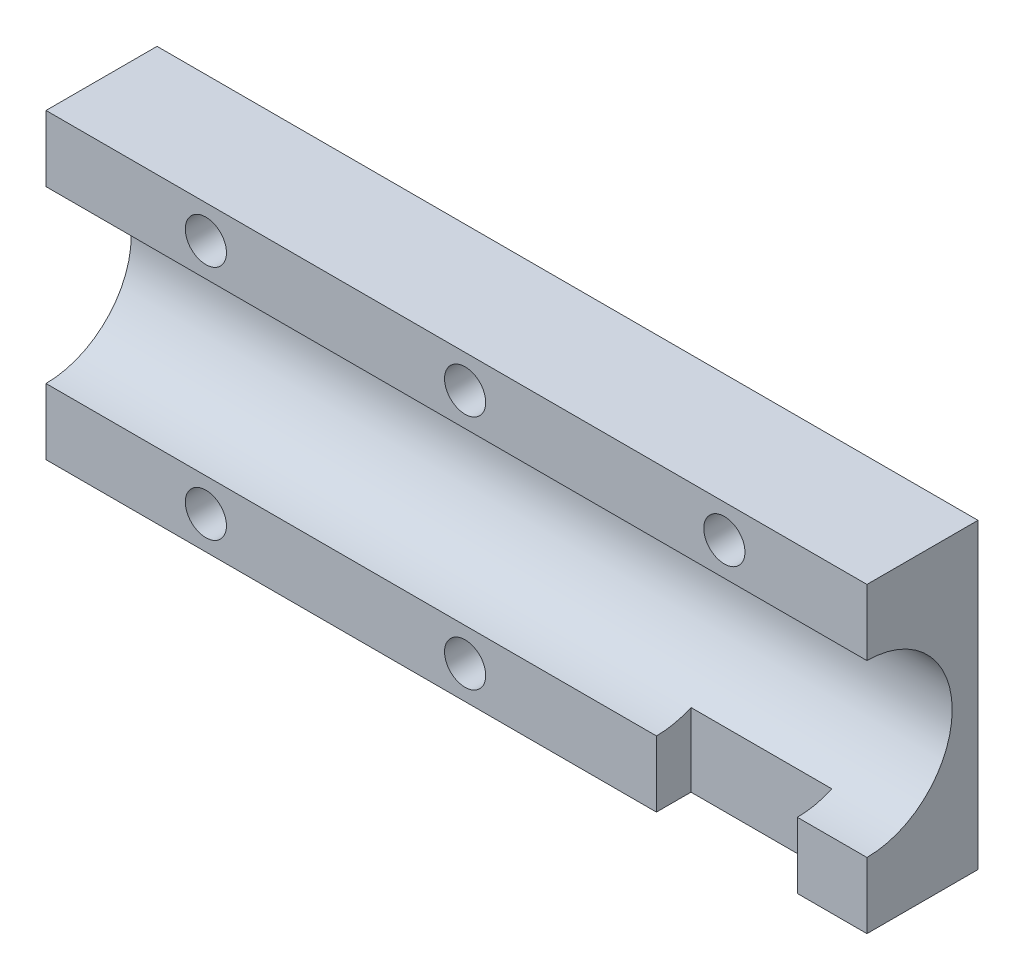
SolidWorks part; units mm, degrees
material "ABS"
ref_plane "X-Y Datum" through (0, 0, 0) normal (0, 0, 1) x (1, 0, 0)
ref_plane "X-Z Datum" through (0, 0, 0) normal (0, 1, 0) x (1, 0, 0)
ref_plane "Y-Z Datum" through (0, 0, 0) normal (1, 0, 0) x (0, 0, -1)
sketch "Sketch1" plane through (0, 0, 0) normal (0, 0, 1) x (1, 0, 0)
  line L1 (-59.055, 22.225) -> (59.055, 22.225)
  line L2 (-59.055, 22.225) -> (-59.055, -22.225)
  line L3 (-59.055, -22.225) -> (59.055, -22.225)
  line L4 (59.055, 22.225) -> (59.055, -22.225)
  line L5 (-59.055, 22.225) -> (59.055, -22.225) construction
  line L6 (-59.055, -22.225) -> (59.055, 22.225) construction
  point P0 (0, 0)
  dimension "D1" = 118.11
  dimension "D2" = 44.45
extrude "Boss-Extrude1" add sketch "Sketch1" along normal blind 2
sketch "Sketch2" plane through (-59.055, 0, 0) normal (-1, 0, 0) x (0, 0, 1)
  line L0 (2, -22.225) -> (0, -22.225) construction
  line L1 (2, 22.225) -> (16.3195, 22.225)
  line L2 (2, 22.225) -> (2, -22.225)
  line L3 (2, -22.225) -> (16.3195, -22.225)
  line L4 (16.3195, 22.225) -> (16.3195, -22.225)
  circle A0 centre (16.3195, 0) radius 12.0269 construction
  circle A1 centre (16.3195, 0) radius 12.0269 construction
  circle A2 centre (16.3195, 0) radius 12.5269
  line M9 (2, -22.225) -> (2, 22.225)
  dimension "D2" = 14.3195
  dimension "D1" = 0.5
extrude "Boss-Extrude2" add sketch "Sketch2" against normal blind 118.11 and the other way blind 2.54 contours A2 L4 L1 L3 M9
sketch "Sketch3" plane through (0, 0, 16.3195) normal (0, 0, 1) x (1, 0, 0)
  line L0 (-57.15, 17.376) -> (57.15, 17.376) construction
  circle A0 centre (0, 17.376) radius 3.025
  dimension "D1" = 6.05
extrude "Cut-Extrude1" cut sketch "Sketch3" against normal blind 8
sketch "Sketch4" [suppressed] plane through (0, 0, 0) normal (0, 0, 1) x (1, 0, 0)
  line L0 (55.5625, -20.6375) -> (65.7225, -30.7975) construction
  line L5 (-65.7225, 20.6375) -> (-55.5625, 20.6375)
  line L6 (-65.7225, 20.6375) -> (-65.7225, 30.7975)
  line L7 (-65.7225, 30.7975) -> (-55.5625, 30.7975)
  line L8 (-55.5625, 20.6375) -> (-55.5625, 30.7975)
  line L9 (55.5625, -30.7975) -> (65.7225, -30.7975)
  line L10 (55.5625, -30.7975) -> (55.5625, -20.6375)
  line L11 (55.5625, -20.6375) -> (65.7225, -20.6375)
  line L12 (65.7225, -30.7975) -> (65.7225, -20.6375)
  line L13 (-65.7225, 30.7975) -> (-55.5625, 20.6375)
  line L14 (49.022, 22.225) -> (-57.15, 22.225) construction
  line L17 (49.022, -22.225) -> (-57.15, -22.225) construction
  line L18 (-55.5625, 30.7975) -> (-46.99, 22.225)
  line L19 (-65.7225, 20.6375) -> (-55.5625, 30.7975)
  line L20 (-65.7225, 20.6375) -> (-57.15, 12.065)
  line L21 (55.5625, -30.7975) -> (46.99, -22.225)
  line L22 (65.7225, -20.6375) -> (55.5625, -30.7975) construction
  line L23 (65.7225, -20.6375) -> (57.15, -12.065)
  line L24 (57.15, -10.7701) -> (49.022, -22.225)
  line L25 (49.022, -22.225) -> (-57.15, -22.225)
  line L26 (-57.15, 22.225) -> (-57.15, 10.3851)
  line L27 (49.022, 22.225) -> (-57.15, 22.225)
  circle A0 centre (60.6425, -25.7175) radius 2 construction
  circle A1 centre (-60.6425, 25.7175) radius 2 construction
  dimension "D1" = 4
  dimension "D2" = 4
  dimension "D3" = 10.16
  dimension "D4" = 10.16
  dimension "D5" = 10.16
  dimension "D6" = 10.16
  dimension "D7" = 1.5875
  dimension "D10" = 1.5875
sketch "Sketch11" plane through (0, 0, 16.3195) normal (0, 0, 1) x (1, 0, 0)
  line L0 (59.055, -12.5269) -> (-61.595, -12.5269) construction
  line L1 (28.1163, -12.5269) -> (48.8246, -12.5269)
  line L2 (28.1163, -12.5269) -> (28.1163, -22.225)
  line L3 (28.1163, -22.225) -> (48.8246, -22.225)
  line L4 (48.8246, -12.5269) -> (48.8246, -22.225)
  line L5 (59.055, -22.225) -> (-61.595, -22.225) construction
extrude "Cut-Extrude4" cut sketch "Sketch11" against normal blind 5.08
sketch "Sketch12" plane through (0, -12.5269, 0) normal (0, -1, 0) x (1, 0, 0)
  line L19 (48.8246, 16.3195) -> (28.1163, 16.3195)
  line L20 (48.8246, 16.3195) -> (48.8246, 11.2395)
  line L21 (48.8246, 11.2395) -> (28.1163, 11.2395)
  line L22 (28.1163, 16.3195) -> (28.1163, 11.2395)
extrude "Cut-Extrude5" cut sketch "Sketch12" against normal blind 2.54
pattern_linear "LPattern1" count 2 spacing 38.1 along (-1, 0, 0) of "Cut-Extrude1"
mirror "Mirror1" about plane through (0, 0, 0) normal (0, 1, 0) of "LPattern1", "Cut-Extrude1"
pattern_linear "LPattern2" count 2 spacing 38.1 along (1, 0, 0) of "Cut-Extrude1"
sketch "Sketch16" plane through (-59.055, 0, 0) normal (-1, 0, 0) x (0, 0, 1)
  line L1 (0, 22.225) -> (2, 22.225)
  line L2 (0, 22.225) -> (0, -22.225)
  line L3 (0, -22.225) -> (2, -22.225)
  line L4 (2, 22.225) -> (2, -22.225)
extrude "Boss-Extrude5" add sketch "Sketch16" along normal blind 2.54
